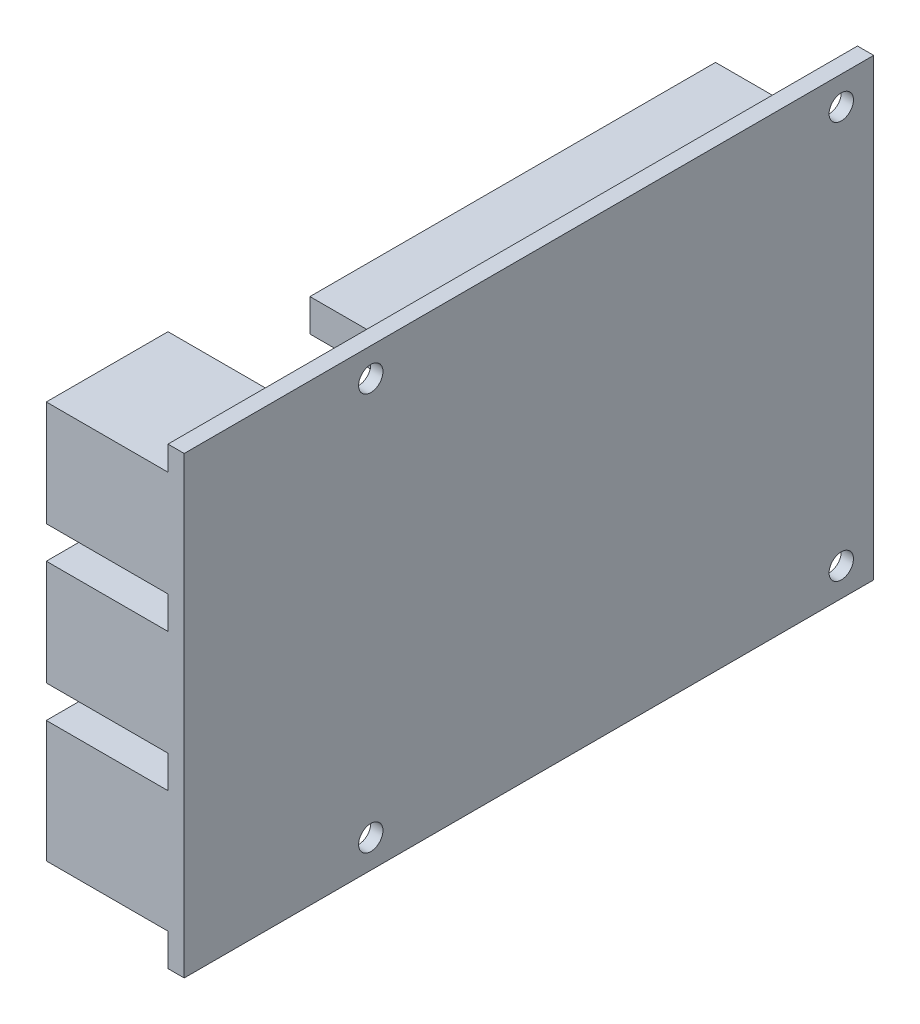
SolidWorks part; units mm, degrees
ref_plane "Plan de face" through (0, 0, 0) normal (0, 0, 1) x (1, 0, 0)
ref_plane "Plan de dessus" through (0, 0, 0) normal (0, 1, 0) x (1, 0, 0)
ref_plane "Plan de droite" through (0, 0, 0) normal (1, 0, 0) x (0, 0, -1)
sketch "Esquisse1" plane through (0, 0, 0) normal (1, 0, 0) x (0, 0, -1)
  line L1 (-42.5, -28) -> (42.5, -28)
  line L2 (-42.5, -28) -> (-42.5, 28)
  line L3 (-42.5, 28) -> (42.5, 28)
  line L4 (42.5, -28) -> (42.5, 28)
  line L5 (-42.5, -28) -> (42.5, 28) construction
  line L6 (-42.5, 28) -> (42.5, -28) construction
  point P0 (0, 0)
  dimension "D1" = 56
  dimension "D2" = 85
extrude "Boss.-Extru.1" add sketch "Esquisse1" along normal blind 2
sketch "Esquisse2" plane through (0, 0, 0) normal (-1, 0, 0) x (0, 0, 1)
  line L0 (42.5, 28) -> (42.5, -28) construction
  line L1 (42.5, -24) -> (22.5, -24)
  line L2 (42.5, -24) -> (42.5, -9)
  line L3 (42.5, -9) -> (22.5, -9)
  line L4 (22.5, -24) -> (22.5, -9)
  line L5 (-42.5, 28) -> (42.5, 28) construction
  line L6 (42.5, -5) -> (27.5, -5)
  line L7 (42.5, -5) -> (42.5, 8)
  line L8 (42.5, 8) -> (27.5, 8)
  line L9 (27.5, -5) -> (27.5, 8)
  line L10 (42.5, 12) -> (27.5, 12)
  line L11 (42.5, 12) -> (42.5, 25)
  line L12 (42.5, 25) -> (27.5, 25)
  line L13 (27.5, 12) -> (27.5, 25)
  dimension "D1" = 15
  dimension "D2" = 13
  dimension "D3" = 20
  dimension "D4" = 15
  dimension "D5" = 15
  dimension "D6" = 13
  dimension "D7" = 3
  dimension "D8" = 4
  dimension "D9" = 4
extrude "Boss.-Extru.2" add sketch "Esquisse2" along normal blind 15 contours L2 L1 L4 L3 | L7 L6 L9 L8 | L11 L10 L13 L12
sketch "Esquisse3" plane through (0, 0, 0) normal (-1, 0, 0) x (0, 0, 1)
  line L0 (-42.5, -28) -> (-42.5, 28) construction
  line L3 (42.5, 28) -> (42.5, 25) construction
  line L4 (-48.6726, 0) -> (45.7389, 0) construction
  circle A0 centre (-38.5, 24.5) radius 1.5
  circle A1 centre (19.5, 24.5) radius 1.5
  circle A6 centre (-38.5, -24.5) radius 1.5
  circle A7 centre (19.5, -24.5) radius 1.5
  dimension "D1" = 3
  dimension "D2" = 3
  dimension "D5" = 24.5
  dimension "D4" = 49
  dimension "D3" = 4
  dimension "D6" = 23
extrude "Enlèv. mat.-Extru.1" cut sketch "Esquisse3" against normal blind 15
sketch "Esquisse5" plane through (0, 0, 0) normal (-1, 0, 0) x (0, 0, 1)
  line L0 (-48.2559, 0) -> (62.0809, 0) construction
  circle A0 centre (19.5, 24.5) radius 2.5
  circle A1 centre (-38.5, 24.5) radius 2.5
  circle A2 centre (-38.5, -24.5) radius 2.5
  circle A3 centre (19.5, -24.5) radius 2.5
  dimension "D1" = 5
  dimension "D2" = 5
extrude "Enlèv. mat.-Extru.2" cut sketch "Esquisse5" against normal blind 0.5
sketch "Esquisse6" plane through (0, 0, 0) normal (-1, 0, 0) x (0, 0, 1)
  line L0 (-42.5, 28) -> (42.5, 28) construction
  line L1 (16, 22) -> (-34, 22)
  line L2 (16, 22) -> (16, 26)
  line L3 (16, 26) -> (-34, 26)
  line L4 (-34, 22) -> (-34, 26)
  circle A0 centre (19.5, 24.5) radius 2.5 construction
  point P4 (-34, 24)
  dimension "D2" = 3.5
  dimension "D1" = 50
  dimension "D3" = 4
  dimension "D4" = 2
extrude "Boss.-Extru.3" add sketch "Esquisse6" along normal blind 9
